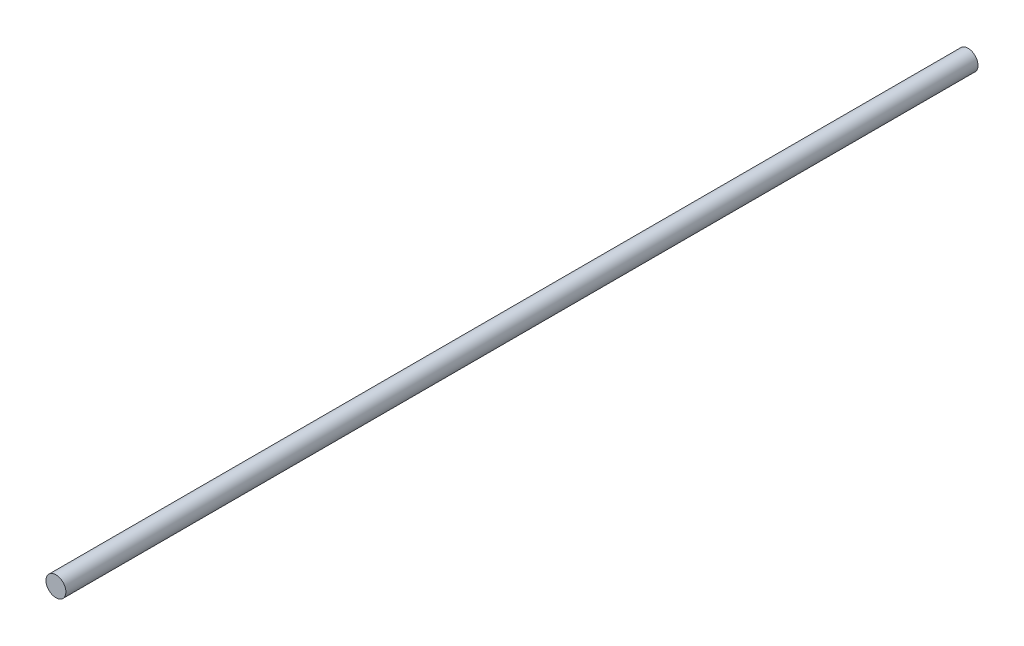
SolidWorks part; units mm, degrees
ref_plane "Front Plane" through (0, 0, 0) normal (0, 0, 1) x (1, 0, 0)
ref_plane "Top Plane" through (0, 0, 0) normal (0, 1, 0) x (1, 0, 0)
ref_plane "Right Plane" through (0, 0, 0) normal (1, 0, 0) x (0, 0, -1)
sketch "Sketch1" plane through (0, 0, 0) normal (0, 0, 1) x (1, 0, 0)
  circle A0 centre (-933, 964) radius 6
  dimension "D1" = 12
extrude "Boss-Extrude1" add sketch "Sketch1" along normal blind 550
